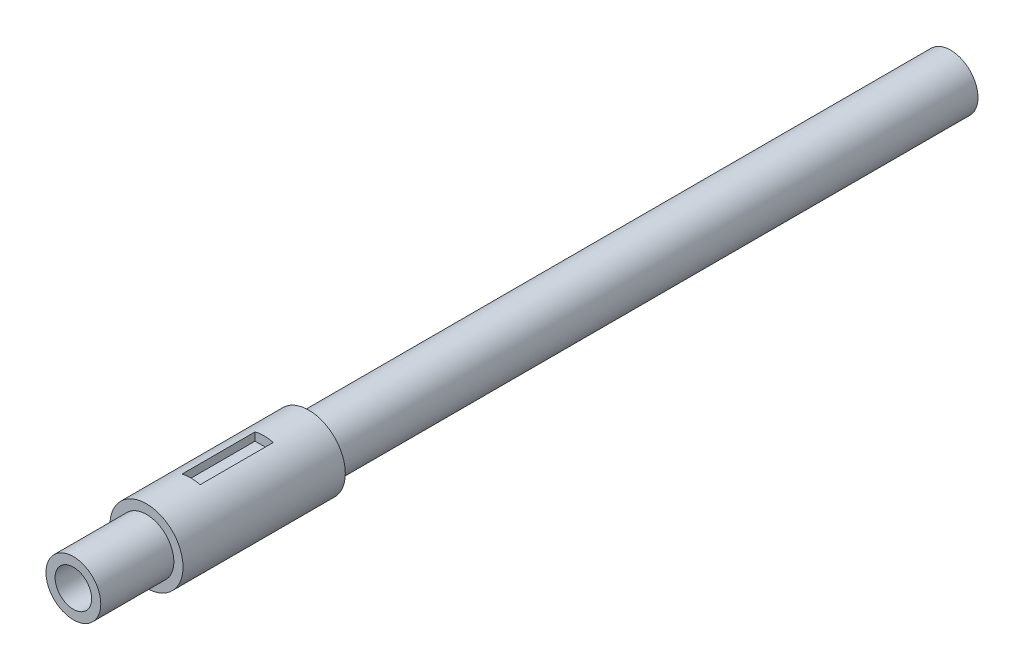
SolidWorks part; units mm, degrees
ref_plane "Front Plane" through (0, 0, 0) normal (0, 0, 1) x (1, 0, 0)
ref_plane "Top Plane" through (0, 0, 0) normal (0, 1, 0) x (1, 0, 0)
ref_plane "Right Plane" through (0, 0, 0) normal (1, 0, 0) x (0, 0, -1)
sketch "Sketch1" plane through (0, 0, 0) normal (0, 0, 1) x (1, 0, 0)
  circle A0 centre (0, 0) radius 12.7
  circle A1 centre (0, 0) radius 6.35
  dimension "D1" = 25.4
  dimension "D2" = 12.7
extrude "Boss-Extrude1" add sketch "Sketch1" against normal blind 304.8
ref_plane "Plane1" through (0, 0, -81.788) normal (0, 0, 1) x (1, 0, 0)
sketch "Sketch3" plane through (0, 0, -81.788) normal (0, 0, 1) x (1, 0, 0)
  circle A0 centre (0, 0) radius 9.525
  circle A1 centre (0, 0) radius 19.05
  dimension "D1" = 19.05
  dimension "D2" = 38.1
extrude "Cut-Extrude2" cut sketch "Sketch3" against normal blind 254
ref_plane "Plane2" through (0, 0, -40.894) normal (0, 0, 1) x (1, 0, 0)
sketch "Sketch4" plane through (0, 0, -40.894) normal (0, 0, 1) x (1, 0, 0)
  line L0 (0, 0) -> (-50000, 0) construction
  line L1 (0, 0) -> (0, 50000) construction
  line L2 (-3.175, 12.2967) -> (-3.175, 15.8527)
  line L3 (-3.175, 15.8527) -> (3.175, 15.8527)
  line L4 (3.175, 15.8527) -> (3.175, 12.2967)
  line L5 (-3.175, 12.2967) -> (-3.175, 9.5027)
  line L6 (-3.175, 9.5027) -> (3.175, 9.5027)
  line L7 (3.175, 9.5027) -> (3.175, 12.2967)
  circle A0 centre (0, 0) radius 12.7 construction
  dimension "D1" = 25.4
  dimension "D2" = 6.35
  dimension "D3" = 3.556
  dimension "D4" = 2.794
extrude "Cut-Extrude3" cut sketch "Sketch4" against normal blind 25.4
ref_plane "Plane3" through (0, 0, -25.4) normal (0, 0, 1) x (1, 0, 0)
sketch "Sketch2" plane through (0, 0, 0) normal (0, 0, 1) x (1, 0, 0)
  circle A0 centre (0, 0) radius 9.525
  circle A1 centre (0, 0) radius 19.05
  dimension "D1" = 19.05
  dimension "D2" = 38.1
extrude "Cut-Extrude5" cut sketch "Sketch2" against normal up to surface (25.4 mm away)
equation "\"D4@Sketch4\"=\"D2@Sketch4\"-\"D3@Sketch4\""
